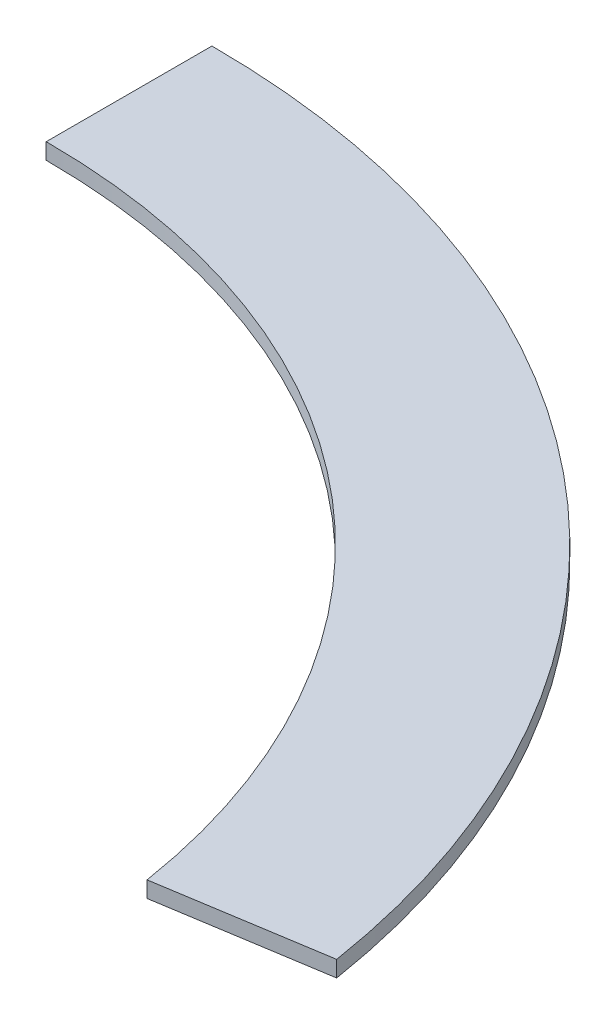
SolidWorks part; units mm, degrees
ref_plane "Front Plane" through (0, 0, 0) normal (0, 0, 1) x (1, 0, 0)
ref_plane "Top Plane" through (0, 0, 0) normal (0, 1, 0) x (1, 0, 0)
ref_plane "Right Plane" through (0, 0, 0) normal (1, 0, 0) x (0, 0, -1)
sketch "Sketch1" plane through (0, 0, 0) normal (0, 1, 0) x (1, 0, 0)
  line L0 (0, 43.252) -> (0, 55.5676)
  line L1 (42.7173, 6.7797) -> (54.8808, 8.7096)
  arc A0 (0, 43.252) -> (42.7173, 6.7797) centre (0, 0) cw
  arc A1 (0, 55.5676) -> (54.8808, 8.7096) centre (0, 0) cw
  dimension "D3" = 12.3156
  dimension "D4" = 55.5676
  dimension "D1" = 61.1323
  dimension "D2" = 78.5398
extrude "Boss-Extrude1" add sketch "Sketch1" along normal blind 1
sketch "Sketch3" plane through (0, 1, 0) normal (0, 1, 0) x (1, 0, 0)
  circle A0 centre (0, 0) radius 53.515
  arc A1 (54.8808, 8.7096) -> (0, 55.5676) centre (0, 0) ccw construction
  line M15 (42.7173, 6.7797) -> (54.8808, 8.7096)
  arc M16 (54.8808, 8.7096) -> (0, 55.5676) centre (0, 0) ccw
  line M17 (0, 55.5676) -> (0, 43.252)
  dimension "D1" = 2.0526
extrude "Cut-Extrude2" cut sketch "Sketch3" against normal through all contours A0 M15 M16 M17
sketch "Sketch2" plane through (0, 1, 0) normal (0, 1, 0) x (1, 0, 0)
  line L0 (18.2791, 39.1996) -> (22.6164, 48.5011)
  line L1 (17.0912, 39.7536) -> (54.3304, 22.3886) construction
  line L2 (0, 53.515) -> (0, 43.252) construction
  line L3 (20.5017, 45.1492) -> (19.4875, 42.9741)
  line L4 (19.9946, 44.0617) -> (20.9009, 43.639)
  line L5 (20.3938, 42.5515) -> (21.4081, 44.7266)
  line L6 (21.4081, 44.7266) -> (20.5017, 45.1492)
  line L7 (20.3938, 42.5515) -> (19.4875, 42.9741)
  line L8 (23.9253, 45.1161) -> (47008.5564, 17146.1233) construction
  line L9 (19.5715, 44.8107) -> (19.1489, 43.9043)
  line L10 (21.324, 42.8901) -> (19.1489, 43.9043)
  line L11 (19.5715, 44.8107) -> (21.7466, 43.7964)
  line L12 (21.7466, 43.7964) -> (21.324, 42.8901)
  arc A1 (42.7173, 6.7797) -> (0, 43.252) centre (0, 0) ccw construction
  arc A3 (52.8536, 8.3879) -> (0, 53.515) centre (0, 0) ccw construction
  point P10 (20.4478, 43.8504)
  dimension "D2" = 1.2
  dimension "D1" = 25
  dimension "D3" = 1
  dimension "D4" = 45
extrude "Cut-Extrude1" [suppressed] cut sketch "Sketch2" against normal through all contours L0 L11 L5 L6 | L3 L11 L0 L6 | L11 L3 L4 L0 | L11 L9 L10 L3 | L10 L0 L4 L3 | L0 L10 L3 L7 | L5 L10 L0 L7 | L10 L5 L4 L0 | L12 L11 L5 L10 | L11 L0 L4 L5
chamfer "Chamfer1" [suppressed] distance 1 angle 45
equation "\"outer_diameter\" = 25mm"
equation "\"D2@Sketch1\"= \"outer_diameter\" * pi"
equation "\"inner diameter\" = 19.459mm"
equation "\"D1@Sketch1\"= \"inner diameter\" * pi"
equation "\"D4@Sketch1\" = \"outer_diameter\" / ( 2 * sin ( 13 ) )"
equation "\"height\" = 12"
equation "\"D3@Sketch1\" = \"height\" / cos ( 13 )"
equation "\"D1@Sketch3\" = 2 / cos ( 13 )"
